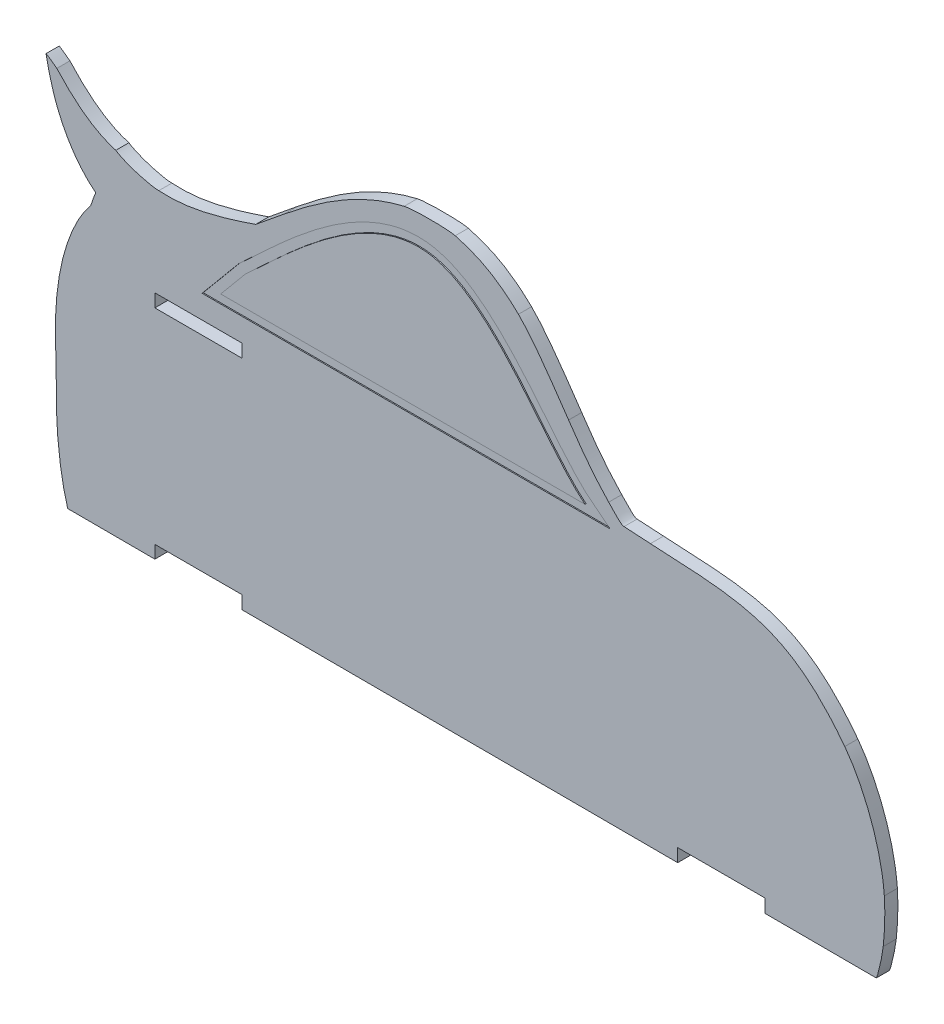
SolidWorks part; units mm, degrees
ref_plane "Front Plane" through (0, 0, 0) normal (0, 0, 1) x (1, 0, 0)
ref_plane "Top Plane" through (0, 0, 0) normal (0, 1, 0) x (1, 0, 0)
ref_plane "Right Plane" through (0, 0, 0) normal (1, 0, 0) x (0, 0, -1)
sketch "Sketch1" plane through (0, 0, 0) normal (0, 0, 1) x (1, 0, 0)
  line L0 (-55.7716, 211.885) -> (-81.3596, 211.9556)
  line L2 (-221.359, 212.342) -> (-221.359, 215.2868)
  line L3 (-221.359, 215.2868) -> (-201.359, 215.2868)
  line L4 (-201.359, 215.2868) -> (-201.359, 212.2868)
  line L5 (-101.3596, 212.0108) -> (-101.3596, 215.0108)
  line L6 (-221.359, 212.342) -> (-241.359, 212.3972)
  line L7 (-101.3596, 215.0108) -> (-81.3596, 215.0108)
  line L8 (-81.3596, 215.0108) -> (-81.3596, 211.9556)
  line L10 (-101.3596, 212.0108) -> (-201.359, 212.2868)
  spline S0 degree 3 poles (-241.359, 212.3972) (-243.4332, 219.2335) (-244.375, 229.5321) (-243.7678, 238.7371) knots 0 0 0 0 1 1 1 1
  spline S1 degree 3 poles (-243.7678, 238.7371) (-245.3417, 253.755) (-242.4421, 267.5573) (-236.0989, 275.2418) knots 0 0 0 0 1 1 1 1
  spline S2 degree 3 poles (-236.0989, 275.2418) (-235.7342, 276.0608) (-235.5376, 276.7436) (-235.6621, 276.7591) knots 0 0 0 0 1 1 1 1
  spline S3 degree 3 poles (-235.6621, 276.7591) (-235.5911, 276.8625) (-235.2608, 277.5971) (-234.9281, 278.3916) knots 0 0 0 0 1 1 1 1
  spline S4 degree 3 poles (-234.9281, 278.3916) (-239.3489, 281.794) (-243.1227, 287.9396) (-245.0285, 294.8402) knots 0 0 0 0 1 1 1 1
  spline S5 degree 3 poles (-245.0285, 294.8402) (-245.5502, 296.5739) (-246.4036, 300.2509) (-246.3109, 300.3657) knots 0 0 0 0 1 1 1 1
  spline S6 degree 3 poles (-246.3109, 300.3657) (-246.298, 300.4284) (-245.1945, 299.6561) (-243.8588, 298.6496) knots 0 0 0 0 1 1 1 1
  spline S7 degree 3 poles (-243.8588, 298.6496) (-239.1398, 293.437) (-234.8805, 290.445) (-230.3133, 289.1342) knots 0 0 0 0 1 1 1 1
  spline S8 degree 3 poles (-230.3133, 289.1342) (-228.4763, 287.8083) (-222.9166, 286.0618) (-220.4553, 286.0375) knots 0 0 0 0 1 1 1 1
  spline S9 degree 3 poles (-220.4553, 286.0375) (-214.5946, 285.692) (-208.6683, 286.8691) (-198.2179, 290.4543) knots 0 0 0 0 1 1 1 1
  spline S10 degree 3 poles (-198.2179, 290.4543) (-196.1734, 292.1185) (-193.2247, 294.5195) (-191.6654, 295.7898) knots 0 0 0 0 1 1 1 1
  spline S11 degree 3 poles (-191.6654, 295.7898) (-181.1234, 304.3777) (-172.6488, 309.0903) (-164.132, 311.1005) knots 0 0 0 0 1 1 1 1
  spline S12 degree 3 poles (-164.132, 311.1005) (-162.0755, 311.5859) (-154.2822, 311.5832) (-152.4129, 311.0969) knots 0 0 0 0 1 1 1 1
  spline S13 degree 3 poles (-152.4129, 311.0969) (-146.792, 309.6333) (-142.5046, 307.167) (-137.902, 302.7496) knots 0 0 0 0 1 1 1 1
  spline S14 degree 3 poles (-137.902, 302.7496) (-135.5531, 300.4952) (-132.3709, 296.2739) (-126.3917, 287.4803) knots 0 0 0 0 1 1 1 1
  spline S15 degree 3 poles (-126.3917, 287.4803) (-122.6489, 281.9759) (-120.6119, 279.3752) (-117.2016, 275.747) knots 0 0 0 0 1 1 1 1
  spline S16 degree 3 poles (-117.2016, 275.747) (-114.7799, 273.1706) (-114.2745, 272.7283) (-113.6733, 272.6591) knots 0 0 0 0 1 1 1 1
  spline S17 degree 3 poles (-113.6733, 272.6591) (-113.2873, 272.6145) (-110.5594, 272.4545) (-107.6112, 272.3033) knots 0 0 0 0 1 1 1 1
  spline S18 degree 3 poles (-107.6112, 272.3033) (-86.3468, 271.2128) (-75.9191, 271.2271) (-63.0082, 254.2734) knots 0 0 0 0 1 1 1 1
  spline S19 degree 3 poles (-63.0082, 254.2734) (-58.7967, 248.7432) (-54.6457, 238.6663) (-53.9302, 229.1289) knots 0 0 0 0 1 1 1 1
  spline S20 degree 3 poles (-53.9302, 229.1289) (-53.7211, 226.3424) (-53.7926, 222.2266) (-54.1879, 218.9296) knots 0 0 0 0 1 1 1 1
  spline S21 degree 3 poles (-54.1879, 218.9296) (-54.4906, 216.404) (-55.3302, 212.7484) (-55.7716, 211.885) knots 0 0 0 0 1 1 1 1
  point P1 (0, 0)
  point P32 (-241.359, 286.0375)
  point P33 (0, 0)
  point P63 (-241.359, 286.0375)
  dimension "D1" = 185.5881
  dimension "D2" = 20
  dimension "D3" = 20
  dimension "D4" = 20
  dimension "D5" = 140
  dimension "D6" = 3
  dimension "D7" = 3
extrude "Boss-Extrude1" add sketch "Sketch1" along normal blind 3 contours S9 S10 S11 S12 S13 S14 S15 S16 S17 S18 S19 S20 S21 L0 L8 L7 L5 L10 L4 L3 L2 L6 S0 S1 S2 S3 S4 S5 S6 S7 S8
sketch "Sketch2" plane through (0, 0, 3) normal (0, 0, 1) x (1, 0, 0)
  line L2 (-221.359, 265.2868) -> (-201.359, 265.2868)
  line L3 (-221.359, 265.2868) -> (-221.359, 262.2868)
  line L4 (-221.359, 262.2868) -> (-201.359, 262.2868)
  line L5 (-201.359, 265.2868) -> (-201.359, 262.2868)
extrude "Cut-Extrude1" cut sketch "Sketch2" against normal blind 10
sketch "Sketch3" plane through (0, 0, 3) normal (0, 0, 1) x (1, 0, 0)
  line L0 (-122.6383, 272.6101) -> (-206.2451, 272.6101)
  line L1 (-116.8681, 270.6101) -> (-210.5151, 270.6101)
  spline S0 degree 3 poles (-200.6414, 279.3345) (-191.1104, 287.9158) (-155.9984, 325.2359) (-131.7242, 279.7686) (-122.6383, 272.6101) knots 0 0 0 0 0.511041 1 1 1 1
  spline S1 degree 1 poles (-200.6414, 279.3345) (-206.2451, 272.6101) knots 0 0 1 1
  spline S2 degree 1 poles (-202.0861, 280.725) (-116.8681, 270.6101) knots 0 0 1 1 construction
  spline S3 degree 1 poles (-202.0861, 280.725) (-210.5151, 270.6101) knots 0 0 1 1 construction
  spline S4 degree 3 poles (-202.0861, 280.725) (-201.7662, 281.013) (-201.1441, 281.5772) (-199.7865, 282.8299) (-197.9642, 284.5333) (-195.5765, 286.7613) (-192.1621, 289.8917) (-187.5077, 293.9651) (-181.4532, 298.6591) (-175.0593, 302.7125) (-168.4305, 305.6697) (-162.7729, 306.8005) (-158.2274, 306.5979) (-153.7738, 305.5391) (-148.618, 302.8642) (-142.9481, 298.2244) (-137.7046, 292.7282) (-132.8403, 286.9258) (-129.0934, 282.2979) (-126.291, 279.0075) (-124.2954, 276.8201) (-122.7336, 275.2967) (-121.7803, 274.4818) (-121.3545, 274.1447) (-121.0326, 273.8913) (-120.1744, 273.2149) (-118.7534, 272.0956) (-117.4971, 271.1057) (-116.8681, 270.6101) knots -0.001903 -0.001903 -0.001903 -0.001903 0.015022 0.031947 0.065797 0.099648 0.133498 0.201198 0.268899 0.3366 0.4043 0.472001 0.505851 0.539701 0.607402 0.675102 0.742803 0.810503 0.878204 0.912054 0.945905 0.979755 0.99668 1.000911 1.005143 1.013605 1.047455 1.081306 1.081306 1.081306 1.081306
  spline S5 degree 3 poles (-210.5151, 270.6101) (-207.7055, 273.9818) (-204.8958, 277.3534) (-202.0861, 280.725) knots -0.01637 -0.01637 -0.01637 -0.01637 1.48783 1.48783 1.48783 1.48783
  dimension "D1" = 2
extrude "Cut-Extrude2" cut sketch "Sketch3" against normal blind 0.25
fillet "Fillet1" radius 490 3 edges at (-243.7678, 238.7371, 1.5)
fillet "Fillet3" radius 20 3 edges at (-235.6621, 276.7591, 1.5)
